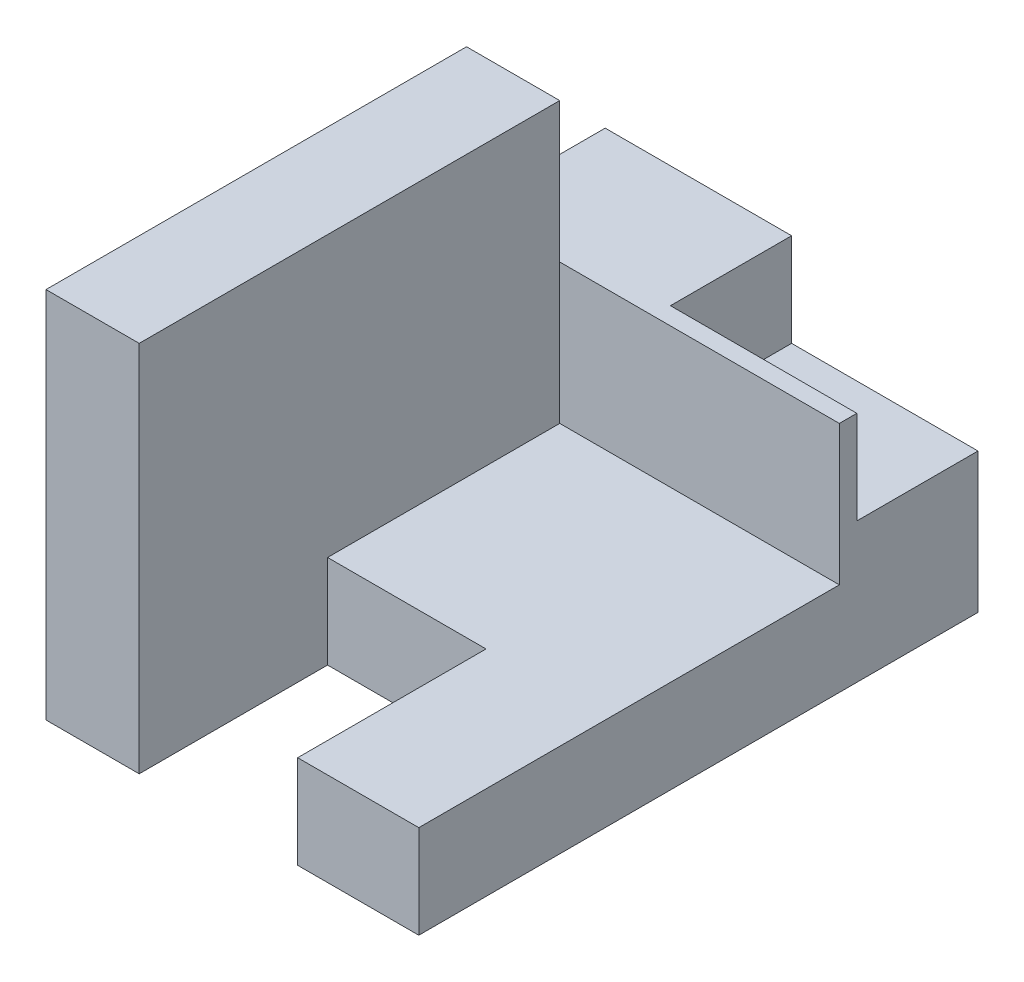
SolidWorks part; units mm, degrees
ref_plane "Front Plane" through (0, 0, 0) normal (0, 0, 1) x (1, 0, 0)
ref_plane "Top Plane" through (0, 0, 0) normal (0, 1, 0) x (1, 0, 0)
ref_plane "Right Plane" through (0, 0, 0) normal (1, 0, 0) x (0, 0, -1)
sketch "Sketch1" plane through (0, 0, 0) normal (0, 0, 1) x (1, 0, 0)
  line L1 (0, 0) -> (40, 0)
  line L2 (0, 0) -> (0, 40)
  line L3 (0, 40) -> (40, 40)
  line L4 (40, 0) -> (40, 40)
  dimension "D1" = 40
  dimension "D2" = 40
extrude "Boss-Extrude1" add sketch "Sketch1" along normal blind 60
sketch "Sketch2" plane through (0, 40, 0) normal (0, 1, 0) x (1, 0, 0)
  line L5 (10, -60) -> (27.004, -60)
  line L6 (10, -60) -> (10, -39.7896)
  line L7 (10, -39.7896) -> (27.004, -39.7896)
  line L8 (27.004, -60) -> (27.004, -39.7896)
extrude "Cut-Extrude1" cut sketch "Sketch2" against normal blind 50
sketch "Sketch3" plane through (0, 40, 0) normal (0, 1, 0) x (1, 0, 0)
  line L1 (10, -60) -> (40, -60)
  line L2 (10, -60) -> (10, -14.8778)
  line L4 (40, -60) -> (40, -14.8778)
  line L8 (10, -14.8778) -> (40, -14.8778)
extrude "Cut-Extrude2" cut sketch "Sketch3" against normal blind 30
sketch "Sketch4" plane through (0, 40, 0) normal (0, 1, 0) x (1, 0, 0)
  line L1 (0, 0) -> (40, 0)
  line L2 (0, 0) -> (0, -14.8778)
  line L3 (0, -14.8778) -> (40, -14.8778)
  line L4 (40, 0) -> (40, -14.8778)
extrude "Cut-Extrude3" cut sketch "Sketch4" against normal blind 15
sketch "Sketch5" plane through (0, 25, 0) normal (0, 1, 0) x (1, 0, 0)
  line L0 (40, 0) -> (0, 0) construction
  line L4 (20, -13) -> (20, 0)
  line L5 (40, -14.8778) -> (40, 0) construction
  line L6 (20, 0) -> (40, 0)
  line L8 (20, -13) -> (40, -13)
  line L9 (40, 0) -> (40, -13)
extrude "Cut-Extrude4" cut sketch "Sketch5" against normal blind 10
